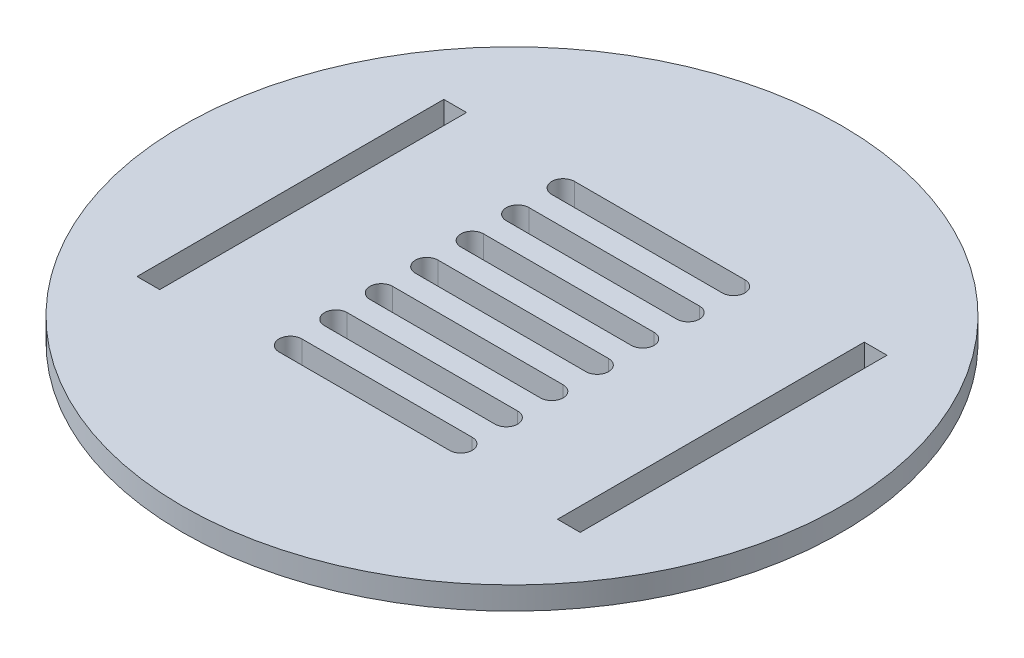
SolidWorks part; units mm, degrees
ref_plane "Front Plane" through (0, 0, 0) normal (0, 0, 1) x (1, 0, 0)
ref_plane "Top Plane" through (0, 0, 0) normal (0, 1, 0) x (1, 0, 0)
ref_plane "Right Plane" through (0, 0, 0) normal (1, 0, 0) x (0, 0, -1)
sketch "Sketch1" plane through (0, 0, 0) normal (0, 1, 0) x (1, 0, 0)
  circle A0 centre (0, 0) radius 58
  dimension "D1" = 116
extrude "Boss-Extrude1" add sketch "Sketch1" along normal blind 4
sketch "Sketch2" plane through (0, 4, 0) normal (0, 1, 0) x (1, 0, 0)
  line L0 (0, 0) -> (37, 0) construction
  line L1 (35, -27) -> (39, -27)
  line L2 (35, -27) -> (35, 27)
  line L3 (35, 27) -> (39, 27)
  line L4 (39, -27) -> (39, 27)
  line L5 (35, -27) -> (39, 27) construction
  line L6 (35, 27) -> (39, -27) construction
  line L7 (0, -2.2) -> (0, 2.2) construction
  line L8 (-35, 27) -> (-39, 27)
  line L9 (-39, -27) -> (-39, 27)
  line L10 (-35, -27) -> (-39, -27)
  line L11 (-35, -27) -> (-35, 27)
  point P0 (37, 0)
  dimension "D1" = 54
  dimension "D2" = 4
  dimension "D3" = 35
extrude "Cut-Extrude1" cut sketch "Sketch2" against normal through all
sketch "Sketch3" plane through (0, 4, 0) normal (0, 1, 0) x (1, 0, 0)
  line L0 (-15, 0) -> (15, 0) construction
  line L1 (-15, 2) -> (15, 2)
  line L2 (-15, -2) -> (15, -2)
  line L3 (-15, -8) -> (15, -8) construction
  line L4 (-15, -6) -> (15, -6)
  line L5 (-15, -10) -> (15, -10)
  line L6 (-15, -16) -> (15, -16) construction
  line L7 (-15, -14) -> (15, -14)
  line L8 (-15, -18) -> (15, -18)
  line L9 (-15, -24) -> (15, -24) construction
  line L10 (-15, -22) -> (15, -22)
  line L11 (-15, -26) -> (15, -26)
  line L12 (-15, 0) -> (15, 0) construction
  line L13 (-15, 2) -> (15, 2)
  line L14 (-15, -2) -> (15, -2)
  line L15 (-15, -8) -> (15, -8) construction
  line L16 (-15, -6) -> (15, -6)
  line L17 (-15, -10) -> (15, -10)
  line L18 (-15, -16) -> (15, -16) construction
  line L19 (-15, -14) -> (15, -14)
  line L20 (-15, -18) -> (15, -18)
  line L21 (-15, 8) -> (15, 8) construction
  line L22 (-15, 10) -> (15, 10)
  line L23 (-15, 6) -> (15, 6)
  line L24 (-15, 0) -> (15, 0) construction
  line L25 (-15, 2) -> (15, 2)
  line L26 (-15, -2) -> (15, -2)
  line L27 (-15, -8) -> (15, -8) construction
  line L28 (-15, -6) -> (15, -6)
  line L29 (-15, -10) -> (15, -10)
  line L30 (-15, 16) -> (15, 16) construction
  line L31 (-15, 18) -> (15, 18)
  line L32 (-15, 14) -> (15, 14)
  line L33 (-15, 8) -> (15, 8) construction
  line L34 (-15, 10) -> (15, 10)
  line L35 (-15, 6) -> (15, 6)
  line L36 (-15, 0) -> (15, 0) construction
  line L37 (-15, 2) -> (15, 2)
  line L38 (-15, -2) -> (15, -2)
  line L39 (-15, 8) -> (15, 8) construction
  line L40 (-15, 10) -> (15, 10)
  line L41 (-15, 6) -> (15, 6)
  line L42 (-15, 16) -> (15, 16) construction
  line L43 (-15, 18) -> (15, 18)
  line L44 (-15, 14) -> (15, 14)
  line L45 (-15, 24) -> (15, 24) construction
  line L46 (-15, 26) -> (15, 26)
  line L47 (-15, 22) -> (15, 22)
  arc A0 (-15, 2) -> (-15, -2) centre (-15, 0) ccw
  arc A1 (15, -2) -> (15, 2) centre (15, 0) ccw
  arc A2 (-15, -6) -> (-15, -10) centre (-15, -8) ccw
  arc A3 (15, -10) -> (15, -6) centre (15, -8) ccw
  arc A4 (-15, -14) -> (-15, -18) centre (-15, -16) ccw
  arc A5 (15, -18) -> (15, -14) centre (15, -16) ccw
  arc A6 (-15, -22) -> (-15, -26) centre (-15, -24) ccw
  arc A7 (15, -26) -> (15, -22) centre (15, -24) ccw
  arc A8 (-15, 2) -> (-15, -2) centre (-15, 0) ccw
  arc A9 (15, -2) -> (15, 2) centre (15, 0) ccw
  arc A10 (-15, -6) -> (-15, -10) centre (-15, -8) ccw
  arc A11 (15, -10) -> (15, -6) centre (15, -8) ccw
  arc A12 (-15, -14) -> (-15, -18) centre (-15, -16) ccw
  arc A13 (15, -18) -> (15, -14) centre (15, -16) ccw
  arc A14 (-15, 10) -> (-15, 6) centre (-15, 8) ccw
  arc A15 (15, 6) -> (15, 10) centre (15, 8) ccw
  arc A16 (-15, 2) -> (-15, -2) centre (-15, 0) ccw
  arc A17 (15, -2) -> (15, 2) centre (15, 0) ccw
  arc A18 (-15, -6) -> (-15, -10) centre (-15, -8) ccw
  arc A19 (15, -10) -> (15, -6) centre (15, -8) ccw
  arc A20 (-15, 18) -> (-15, 14) centre (-15, 16) ccw
  arc A21 (15, 14) -> (15, 18) centre (15, 16) ccw
  arc A22 (-15, 10) -> (-15, 6) centre (-15, 8) ccw
  arc A23 (15, 6) -> (15, 10) centre (15, 8) ccw
  arc A24 (-15, 2) -> (-15, -2) centre (-15, 0) ccw
  arc A25 (15, -2) -> (15, 2) centre (15, 0) ccw
  arc A26 (-15, 10) -> (-15, 6) centre (-15, 8) ccw
  arc A27 (15, 6) -> (15, 10) centre (15, 8) ccw
  arc A28 (-15, 18) -> (-15, 14) centre (-15, 16) ccw
  arc A29 (15, 14) -> (15, 18) centre (15, 16) ccw
  arc A30 (-15, 26) -> (-15, 22) centre (-15, 24) ccw
  arc A31 (15, 22) -> (15, 26) centre (15, 24) ccw
  point P2 (0, 0)
  point P13 (0, -8)
  point P20 (0, -16)
  point P27 (0, -24)
  point P34 (0, 0)
  point P41 (0, -8)
  point P48 (0, -16)
  point P55 (0, 8)
  point P62 (0, 0)
  point P69 (0, -8)
  point P76 (0, 16)
  point P83 (0, 8)
  point P90 (0, 0)
  point P97 (0, 8)
  point P104 (0, 16)
  point P111 (0, 24)
  dimension "D1" = 30
  dimension "D2" = 4
  dimension "D3" = 4
  dimension "D4" = 4
extrude "Cut-Extrude2" cut sketch "Sketch3" against normal blind 4 contours L23 A15 L22 A14 | L32 A21 L31 A20 | L5 A3 L4 A2 | L11 A7 L10 A6 | L1 A1 L2 A0 | L46 A31 L47 A30 | L7 A5 L8 A4
